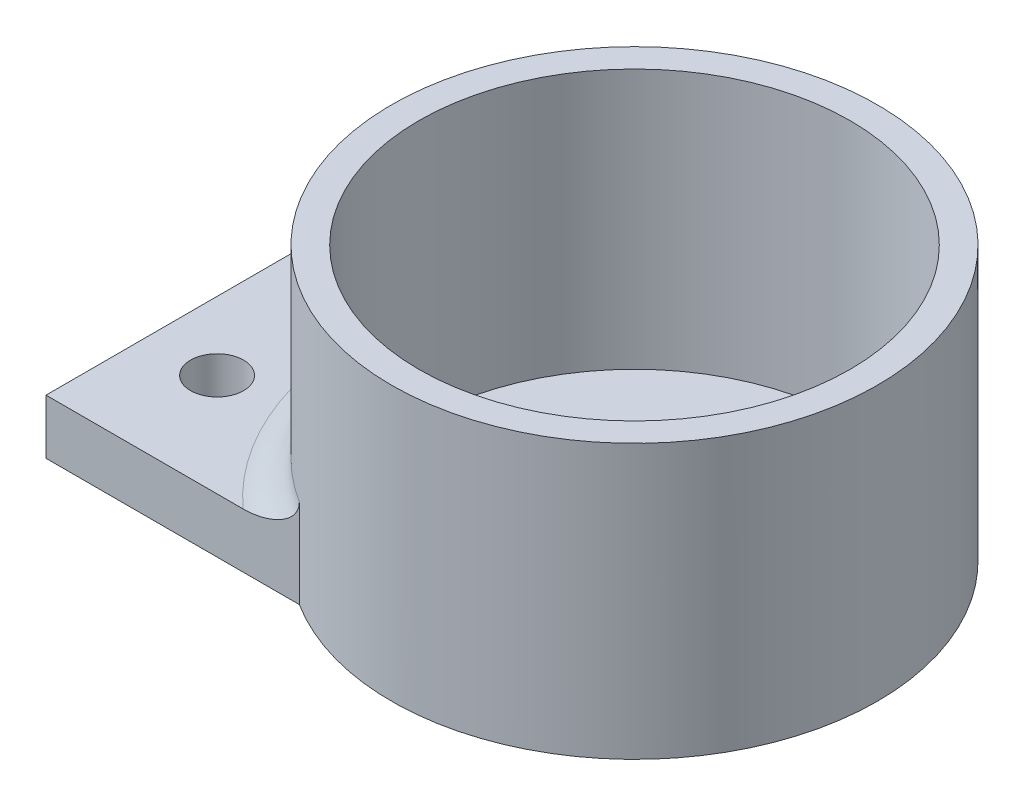
SolidWorks part; units mm, degrees
ref_plane "Front Plane" through (0, 0, 0) normal (0, 0, 1) x (1, 0, 0)
ref_plane "Top Plane" through (0, 0, 0) normal (0, 1, 0) x (1, 0, 0)
ref_plane "Right Plane" through (0, 0, 0) normal (1, 0, 0) x (0, 0, -1)
sketch "Sketch1" plane through (0, 0, 0) normal (0, 1, 0) x (1, 0, 0)
  circle A0 centre (0, 0) radius 12.6
  circle A1 centre (0, 0) radius 14.2
  dimension "D1" = 25.2
  dimension "D2" = 1.6
extrude "Boss-Extrude1" add sketch "Sketch1" along normal blind 16
sketch "Sketch2" plane through (0, 0, 0) normal (0, -1, 0) x (-1, 0, 0)
  line L1 (22.4, -12) -> (6.4, -12)
  line L2 (22.4, -12) -> (22.4, 12)
  line L3 (22.4, 12) -> (6.4, 12)
  line L4 (6.4, -12) -> (6.4, 12)
  circle A0 centre (0, 0) radius 12.6 construction
  circle A1 centre (0, 0) radius 12.2
  point P4 (6.4, 0)
  circle M4 centre (0, 0) radius 14.2
  dimension "D1" = 24
  dimension "D2" = 16
  dimension "D3" = 0
  dimension "D4" = 6.4
extrude "Boss-Extrude2" add sketch "Sketch2" against normal blind 3.2 contours L2 L3 L1 M4
sketch "Sketch3" plane through (0, 0, 0) normal (0, -1, 0) x (-1, 0, 0)
  line L0 (22.4, -12) -> (22.4, 12) construction
  circle A0 centre (18.4, 6) radius 1.55
  circle A1 centre (18.4, -6) radius 1.55
  point P6 (22.4, 0)
  dimension "D1" = 3.1
  dimension "D2" = 3.1
  dimension "D3" = 12
  dimension "D4" = 4
  dimension "D5" = 4
  dimension "D6" = 6
extrude "Cut-Extrude1" cut sketch "Sketch3" against normal blind 10
fillet "Fillet1" radius 2 1 edges at (-14.2, 3.2, 0)
sketch "Sketch4" plane through (0, 0, 0) normal (0, -1, 0) x (-1, 0, 0)
  circle A0 centre (0, 0) radius 12.6
  circle A1 centre (0, 0) radius 3.8
  dimension "D1" = 7.6
extrude "Boss-Extrude3" add sketch "Sketch4" against normal blind 0.8
equation "\"D5@Sketch3\"=\"D4@Sketch3\""
equation "\"D1@Sketch1\"=0.8*31.5"
